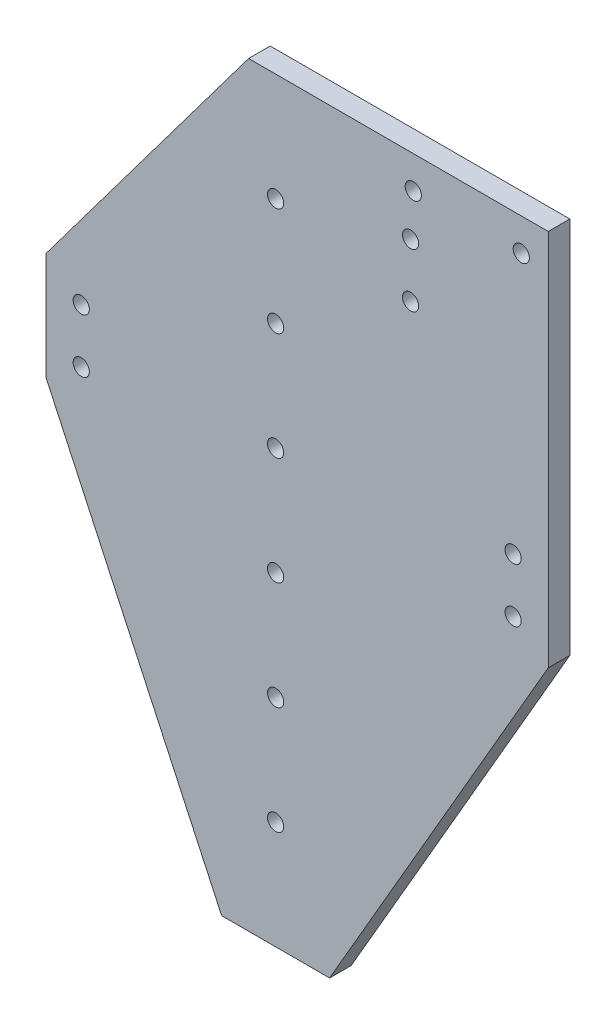
SolidWorks part; units mm, degrees
ref_plane "前视基准面" through (0, 0, 0) normal (0, 0, 1) x (1, 0, 0)
ref_plane "上视基准面" through (0, 0, 0) normal (0, 1, 0) x (1, 0, 0)
ref_plane "右视基准面" through (0, 0, 0) normal (1, 0, 0) x (0, 0, -1)
other "Configuration Table"
sketch "草图1" plane through (0, 0, 0) normal (0, 0, 1) x (1, 0, 0)
  line L0 (0, 0) -> (0, 70)
  line L4 (-46.5, -70) -> (-46.5, 70) construction
  line L5 (-93, 10) -> (-50.5, 10) construction
  line L6 (-86.5, 10) -> (-86.5, 0) construction
  line L7 (-93, 0) -> (-60.5, -70)
  line L8 (-60.5, -70) -> (-40.5, -70)
  line L9 (-40.5, -70) -> (0, 0)
  line L10 (-93, 0) -> (0, 0) construction
  line L11 (-25.5, 56) -> (-25.5, 46) construction
  line L12 (-50.5, 10) -> (-50.5, 30) construction
  line L13 (0, 64) -> (-5, 64) construction
  line L14 (-5, 64) -> (-25, 64) construction
  line L16 (-55.5, 70) -> (0, 70)
  line L18 (-93, 0) -> (-93, 20)
  line L19 (-93, 20) -> (-55.5, 70)
  line L20 (-25.5, 56) -> (-25.5, 70) construction
  line L21 (-50.5, -70) -> (-50.5, -30) construction
  line L22 (-50.5, 50) -> (-50.5, 70) construction
  circle A0 centre (-86.5, 15) radius 1.5
  circle A1 centre (-86.5, 5) radius 1.5
  circle A2 centre (-6.5, 5) radius 1.5
  circle A3 centre (-6.5, 15) radius 1.5
  circle A4 centre (-25.5, 56) radius 1.5
  circle A5 centre (-25.5, 46) radius 1.5
  circle A6 centre (-50.5, 10) radius 1.5
  circle A7 centre (-50.5, 30) radius 1.5
  circle A8 centre (-50.5, 50) radius 1.5
  circle A9 centre (-50.5, -10) radius 1.5
  circle A10 centre (-50.5, -30) radius 1.5
  circle A11 centre (-5, 64) radius 1.5
  circle A12 centre (-25, 64) radius 1.5
  circle A13 centre (-50.5, -50) radius 1.5
  point P4 (-46.5, 0)
  point P17 (-86.5, 5)
  point P48 (-93, 10)
  dimension "D1" = 3
  dimension "D3" = 4
  dimension "D4" = 80
  dimension "D10" = 3
  dimension "D12" = 93
  dimension "D13" = 3
  dimension "D17" = 20
  dimension "D21" = 3
  dimension "D2" = 20
  dimension "D5" = 70
  dimension "D6" = 10
  dimension "D7" = 70
  dimension "D9" = 10
  dimension "D11" = 5
  dimension "D15" = 20
  dimension "D18" = 5
  dimension "D19" = 6
  dimension "D20" = 20
  dimension "D22" = 21
  dimension "D23" = 8
  dimension "D8" = 2
  dimension "D14" = 3
  dimension "D16" = 4
extrude "凸台-拉伸1" add sketch "草图1" along normal blind 4
